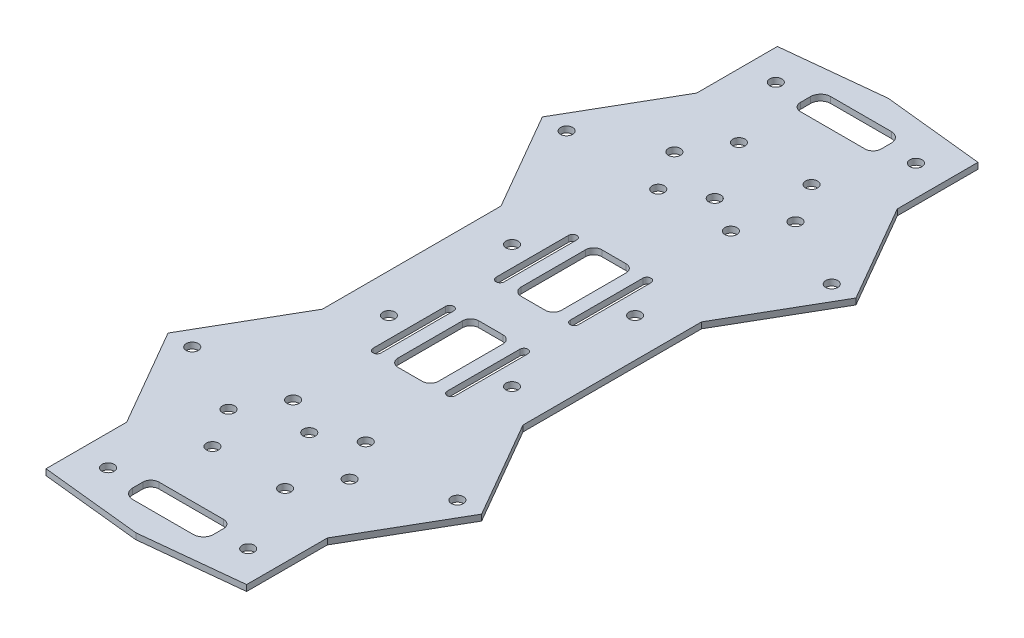
SolidWorks part; units mm, degrees
other "TopFrame"
material "Thornel Mat VMA"
ref_plane "Front Plane" through (0, 0, 0) normal (0, 0, 1) x (1, 0, 0)
ref_plane "Top Plane" through (0, 0, 0) normal (0, 1, 0) x (1, 0, 0)
ref_plane "Right Plane" through (0, 0, 0) normal (1, 0, 0) x (0, 0, -1)
sketch "Sketch1" plane through (0, 0, 0) normal (0, 1, 0) x (1, 0, 0)
  line L0 (-9.2, 6.25) -> (-9.2, 24.25) construction
  line L1 (-3, 5.25) -> (3, 5.25)
  line L2 (-5, 7.25) -> (-5, 23.25)
  line L3 (-3, 25.25) -> (3, 25.25)
  line L4 (5, 7.25) -> (5, 23.25)
  line L5 (-5, 5.25) -> (5, 25.25) construction
  line L6 (-5, 25.25) -> (5, 5.25) construction
  line L11 (-10.2, 6.25) -> (-10.2, 24.25)
  line L12 (-8.2, 6.25) -> (-8.2, 24.25)
  line L13 (0, 5.25) -> (0, 25.25) construction
  line L14 (9.2, 6.25) -> (9.2, 24.25) construction
  line L15 (10.2, 6.25) -> (10.2, 24.25)
  line L16 (8.2, 6.25) -> (8.2, 24.25)
  line L17 (-3, 0) -> (3, 0) construction
  line L18 (0, -5.25) -> (0, -25.25) construction
  line L19 (-5, -25.25) -> (5, -5.25) construction
  line L20 (-5, -5.25) -> (5, -25.25) construction
  line L21 (5, -7.25) -> (5, -23.25)
  line L22 (-3, -25.25) -> (3, -25.25)
  line L23 (-5, -7.25) -> (-5, -23.25)
  line L24 (-3, -5.25) -> (3, -5.25)
  line L25 (9.2, -6.25) -> (9.2, -24.25) construction
  line L26 (10.2, -6.25) -> (10.2, -24.25)
  line L27 (8.2, -6.25) -> (8.2, -24.25)
  line L28 (-9.2, -6.25) -> (-9.2, -24.25) construction
  line L29 (-10.2, -6.25) -> (-10.2, -24.25)
  line L30 (-8.2, -6.25) -> (-8.2, -24.25)
  line L31 (0, 93.25) -> (-24.863, 90.6368)
  line L32 (-24.863, 90.6368) -> (-24.863, 70.6368)
  line L33 (-24.863, 70.6368) -> (-38.863, 46.3881)
  line L34 (-38.863, 46.3881) -> (-24.863, 22.1394)
  line L35 (-24.863, 22.1394) -> (-24.863, -22.1394)
  line L36 (24.863, 22.1394) -> (24.863, -22.1394)
  line L37 (38.863, 46.3881) -> (24.863, 22.1394)
  line L38 (24.863, 70.6368) -> (38.863, 46.3881)
  line L39 (24.863, 90.6368) -> (24.863, 70.6368)
  line L40 (0, 93.25) -> (24.863, 90.6368)
  line L41 (0, -93.25) -> (24.863, -90.6368)
  line L42 (24.863, -90.6368) -> (24.863, -70.6368)
  line L43 (24.863, -70.6368) -> (38.863, -46.3881)
  line L44 (38.863, -46.3881) -> (24.863, -22.1394)
  line L45 (-38.863, -46.3881) -> (-24.863, -22.1394)
  line L46 (-24.863, -70.6368) -> (-38.863, -46.3881)
  line L47 (-24.863, -90.6368) -> (-24.863, -70.6368)
  line L48 (0, -93.25) -> (-24.863, -90.6368)
  arc A0 (-3, 5.25) -> (-5, 7.25) centre (-3, 7.25) cw
  arc A1 (3, 5.25) -> (5, 7.25) centre (3, 7.25) ccw
  arc A2 (3, 25.25) -> (5, 23.25) centre (3, 23.25) cw
  arc A3 (-5, 23.25) -> (-3, 25.25) centre (-3, 23.25) cw
  arc A4 (-10.2, 6.25) -> (-8.2, 6.25) centre (-9.2, 6.25) ccw
  arc A5 (-8.2, 24.25) -> (-10.2, 24.25) centre (-9.2, 24.25) ccw
  arc A6 (10.2, 6.25) -> (8.2, 6.25) centre (9.2, 6.25) cw
  arc A7 (8.2, 24.25) -> (10.2, 24.25) centre (9.2, 24.25) cw
  arc A8 (-5, -23.25) -> (-3, -25.25) centre (-3, -23.25) ccw
  arc A9 (3, -25.25) -> (5, -23.25) centre (3, -23.25) ccw
  arc A10 (3, -5.25) -> (5, -7.25) centre (3, -7.25) cw
  arc A11 (-3, -5.25) -> (-5, -7.25) centre (-3, -7.25) ccw
  arc A12 (10.2, -6.25) -> (8.2, -6.25) centre (9.2, -6.25) ccw
  arc A13 (8.2, -24.25) -> (10.2, -24.25) centre (9.2, -24.25) ccw
  arc A14 (-10.2, -6.25) -> (-8.2, -6.25) centre (-9.2, -6.25) cw
  arc A15 (-8.2, -24.25) -> (-10.2, -24.25) centre (-9.2, -24.25) cw
  circle A16 centre (0, 50.25) radius 1.5
  circle A17 centre (-9, 45.25) radius 1.5
  circle A18 centre (-15, 55.25) radius 1.5
  circle A19 centre (-9, 65.25) radius 1.5
  circle A20 centre (9, 45.25) radius 1.5
  circle A21 centre (9, 65.25) radius 1.5
  circle A22 centre (15, 55.25) radius 1.5
  circle A23 centre (-15.25, 15.25) radius 1.5
  circle A24 centre (15.25, 15.25) radius 1.5
  circle A25 centre (-32.863, 46.3881) radius 1.5
  circle A26 centre (-17.363, 82.75) radius 1.5
  circle A27 centre (32.863, 46.3881) radius 1.5
  circle A28 centre (17.363, 82.75) radius 1.5
  circle A29 centre (-15.25, -15.25) radius 1.5
  circle A30 centre (15.25, -15.25) radius 1.5
  circle A31 centre (32.863, -46.3881) radius 1.5
  circle A32 centre (9, -45.25) radius 1.5
  circle A33 centre (-32.863, -46.3881) radius 1.5
  circle A34 centre (-9, -45.25) radius 1.5
  circle A35 centre (15, -55.25) radius 1.5
  circle A36 centre (0, -50.25) radius 1.5
  circle A37 centre (-15, -55.25) radius 1.5
  circle A38 centre (-9, -65.25) radius 1.5
  circle A39 centre (9, -65.25) radius 1.5
  circle A40 centre (17.363, -82.75) radius 1.5
  circle A41 centre (-17.363, -82.75) radius 1.5
  point P0 (0, 15.25)
  point P19 (-9.2, 15.25)
  point P25 (-9.2, 25.25)
  point P26 (-9.2, 5.25)
  point P31 (9.2, 15.25)
  point P58 (9.2, -15.25)
  point P65 (-9.2, -15.25)
  point P70 (0, -15.25)
  point P83 (24.863, 0)
  point P84 (-24.863, 0)
  dimension "D4" = 2
  dimension "D6" = 1
  dimension "D15" = 3
  dimension "D16" = 25
  dimension "D17" = 20
  dimension "D18" = 9
  dimension "D19" = 10
  dimension "D21" = 10
  dimension "D23" = 3
  dimension "D24" = 3
  dimension "D25" = 3
  dimension "D26" = 30.5
  dimension "D27" = 3
  dimension "D28" = 6
  dimension "D29" = 3
  dimension "D30" = 7.5
  dimension "D31" = 3
  dimension "D32" = 57.5
  dimension "D33" = 30.5
  dimension "D34" = 30.5
  dimension "D1" = 10
  dimension "D2" = 20
  dimension "D3" = 5.25
  dimension "D5" = 20
  dimension "D7" = 3.2
  dimension "D8" = 25
  dimension "D9" = 68
  dimension "D10" = 20
  dimension "D11" = 96
  dimension "D12" = 28
  dimension "D13" = 150
  dimension "D14" = 120
  dimension "D20" = 6
  dimension "D22" = 6
extrude "Boss-Extrude1" add sketch "Sketch1" along normal blind 1.5
sketch "Sketch2" plane through (0, 1.5, 0) normal (0, 1, 0) x (1, 0, 0)
  line L0 (0, 0) -> (9, 0) construction
  line L1 (-8, 79.5) -> (8, 79.5)
  line L2 (-10, 81.5) -> (-10, 84)
  line L3 (-7.5, 86.5) -> (7.5, 86.5)
  line L4 (10, 81.5) -> (10, 84)
  line L5 (-10, 79.5) -> (10, 86.5) construction
  line L6 (-10, 86.5) -> (10, 79.5) construction
  line L7 (-10, -86.5) -> (10, -79.5) construction
  line L8 (-10, -79.5) -> (10, -86.5) construction
  line L9 (10, -81.5) -> (10, -84)
  line L10 (-7.5, -86.5) -> (7.5, -86.5)
  line L11 (-10, -81.5) -> (-10, -84)
  line L12 (-8, -79.5) -> (8, -79.5)
  arc A0 (8, 79.5) -> (10, 81.5) centre (8, 81.5) ccw
  arc A1 (-8, 79.5) -> (-10, 81.5) centre (-8, 81.5) cw
  arc A2 (7.5, 86.5) -> (10, 84) centre (7.5, 84) cw
  arc A3 (-10, 84) -> (-7.5, 86.5) centre (-7.5, 84) cw
  arc A4 (-10, -84) -> (-7.5, -86.5) centre (-7.5, -84) ccw
  arc A5 (7.5, -86.5) -> (10, -84) centre (7.5, -84) ccw
  arc A6 (-8, -79.5) -> (-10, -81.5) centre (-8, -81.5) ccw
  arc A7 (8, -79.5) -> (10, -81.5) centre (8, -81.5) cw
  point P0 (0, 83)
  point P36 (0, -83)
  dimension "D3" = 2
  dimension "D5" = 2.5
  dimension "D1" = 20
  dimension "D2" = 7
  dimension "D4" = 79.5
extrude "Cut-Extrude1" cut sketch "Sketch2" against normal up to surface (1.5 mm away) up to face at (17.363, 0, 84.25)
